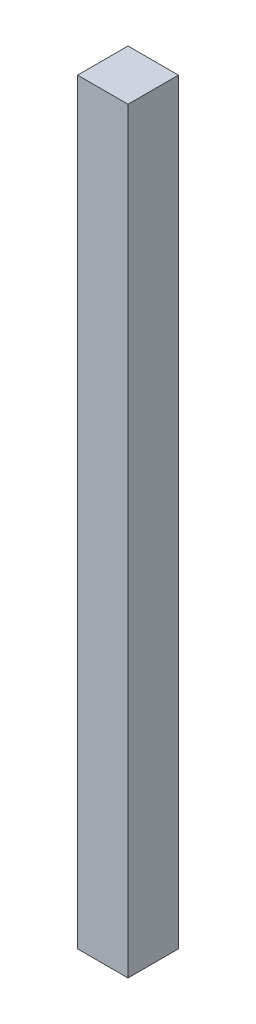
SolidWorks part; units mm, degrees
ref_plane "Front Plane" through (0, 0, 0) normal (0, 0, 1) x (1, 0, 0)
ref_plane "Top Plane" through (0, 0, 0) normal (0, 1, 0) x (1, 0, 0)
ref_plane "Right Plane" through (0, 0, 0) normal (1, 0, 0) x (0, 0, -1)
sketch "Sketch1" plane through (0, 0, 0) normal (0, 1, 0) x (1, 0, 0)
  line L1 (0.5, -0.5) -> (-0.5, -0.5)
  line L2 (0.5, -0.5) -> (0.5, 0.5)
  line L3 (0.5, 0.5) -> (-0.5, 0.5)
  line L4 (-0.5, -0.5) -> (-0.5, 0.5)
  point P0 (0, 0)
  point P7 (0, 0.5)
  point P9 (-0.5, 0)
  dimension "D1" = 1
  dimension "D2" = 1
extrude "Boss-Extrude1" add sketch "Sketch1" along normal blind 15
